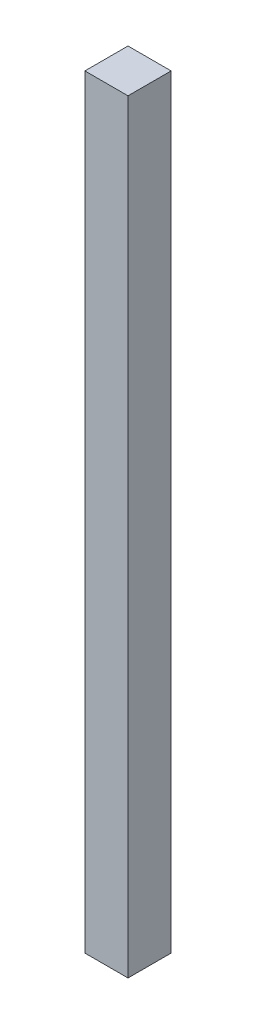
SolidWorks part; units mm, degrees
ref_plane "Front Plane" through (0, 0, 0) normal (0, 0, 1) x (1, 0, 0)
ref_plane "Top Plane" through (0, 0, 0) normal (0, 1, 0) x (1, 0, 0)
ref_plane "Right Plane" through (0, 0, 0) normal (1, 0, 0) x (0, 0, -1)
sketch "Sketch1" plane through (0, 0, 0) normal (0, 1, 0) x (1, 0, 0)
  line L1 (0, 0) -> (25.4, 0)
  line L2 (0, 0) -> (0, 25.4)
  line L3 (0, 25.4) -> (25.4, 25.4)
  line L4 (25.4, 0) -> (25.4, 25.4)
  dimension "D1" = 25.4
extrude "Boss-Extrude1" add sketch "Sketch1" along normal blind 450
